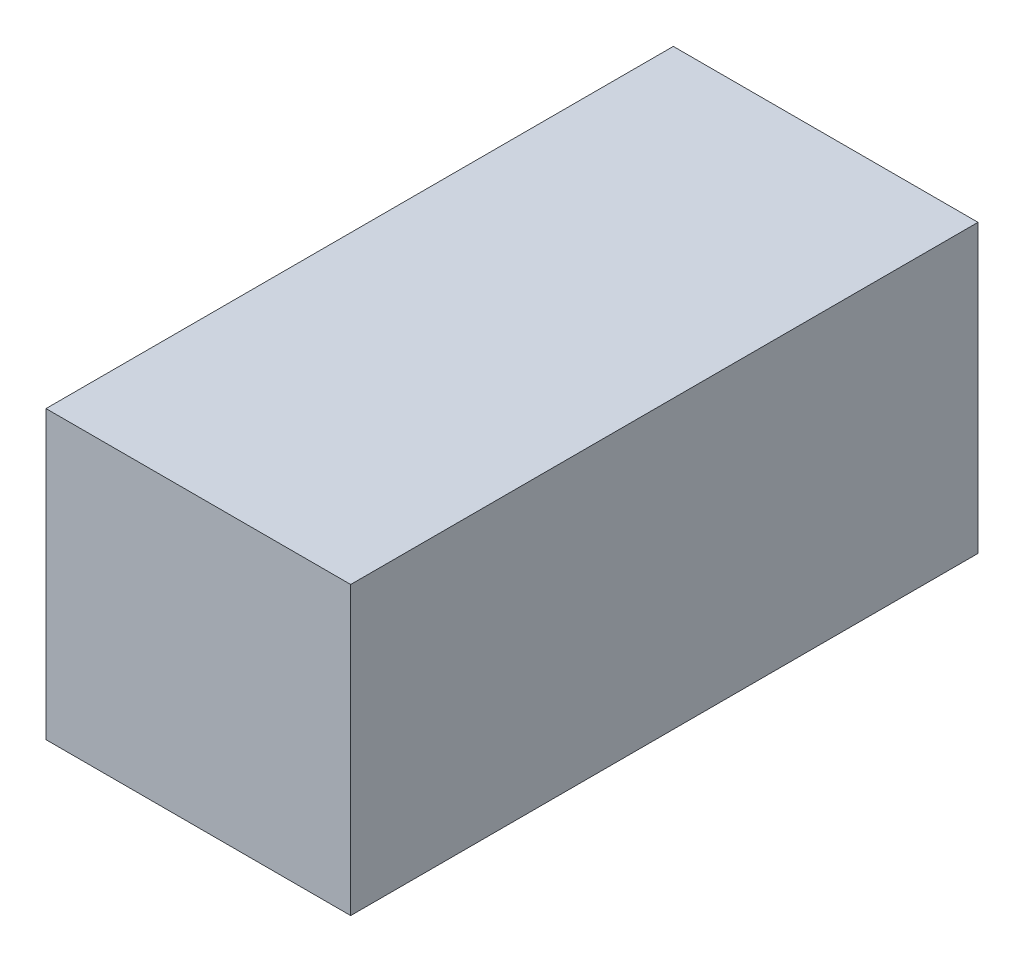
SolidWorks part; units mm, degrees
ref_plane "Front Plane" through (0, 0, 0) normal (0, 0, 1) x (1, 0, 0)
ref_plane "Top Plane" through (0, 0, 0) normal (0, 1, 0) x (1, 0, 0)
ref_plane "Right Plane" through (0, 0, 0) normal (1, 0, 0) x (0, 0, -1)
sketch "Sketch1" plane through (0, 0, 0) normal (0, 1, 0) x (1, 0, 0)
  line L1 (14.847, 11.2383) -> (23.483, 11.2383)
  line L2 (14.847, 11.2383) -> (14.847, -6.5417)
  line L3 (14.847, -6.5417) -> (23.483, -6.5417)
  line L4 (23.483, 11.2383) -> (23.483, -6.5417)
  line L5 (14.847, 11.2383) -> (23.483, -6.5417) construction
  line L6 (14.847, -6.5417) -> (23.483, 11.2383) construction
  point P4 (19.165, 2.3483)
  dimension "D1" = 17.78
  dimension "D2" = 8.636
extrude "Boss-Extrude1" add sketch "Sketch1" along normal blind 8.128
